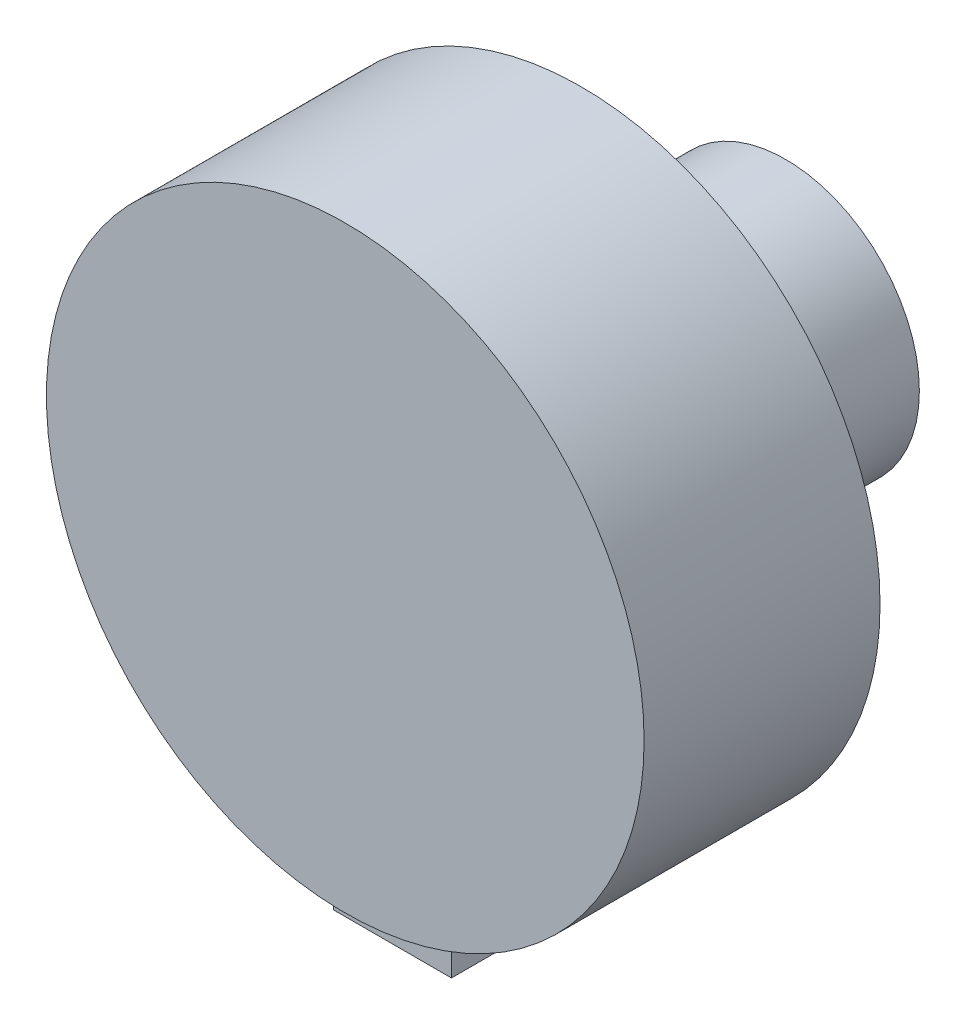
SolidWorks part; units mm, degrees
ref_plane "Front Plane" through (0, 0, 0) normal (0, 0, 1) x (1, 0, 0)
ref_plane "Top Plane" through (0, 0, 0) normal (0, 1, 0) x (1, 0, 0)
ref_plane "Right Plane" through (0, 0, 0) normal (1, 0, 0) x (0, 0, -1)
sketch "Sketch1" plane through (0, 0, 0) normal (0, 0, 1) x (1, 0, 0)
  circle A0 centre (0, 0) radius 48.26
  dimension "D1" = 96.52
extrude "Boss-Extrude1" add sketch "Sketch1" along normal blind 38.1
sketch "Sketch2" plane through (0, 0, 0) normal (0, 0, -1) x (-1, 0, 0)
  circle A0 centre (0, 0) radius 21.59
  dimension "D1" = 43.18
extrude "Boss-Extrude2" add sketch "Sketch2" along normal blind 33.02
sketch "Sketch3" plane through (0, 0, 0) normal (0, 1, 0) x (1, 0, 0)
  line L0 (-48.26, 0) -> (48.26, -38.1) construction
  line L2 (-9.525, -30.48) -> (9.525, -30.48)
  line L3 (-9.525, -30.48) -> (-9.525, -7.62)
  line L4 (-9.525, -7.62) -> (9.525, -7.62)
  line L5 (9.525, -30.48) -> (9.525, -7.62)
  line L6 (-9.525, -30.48) -> (9.525, -7.62) construction
  line L7 (-9.525, -7.62) -> (9.525, -30.48) construction
  point P4 (0, -19.05)
  dimension "D1" = 19.05
  dimension "D2" = 22.86
extrude "Boss-Extrude3" add sketch "Sketch3" against normal blind 56.388
